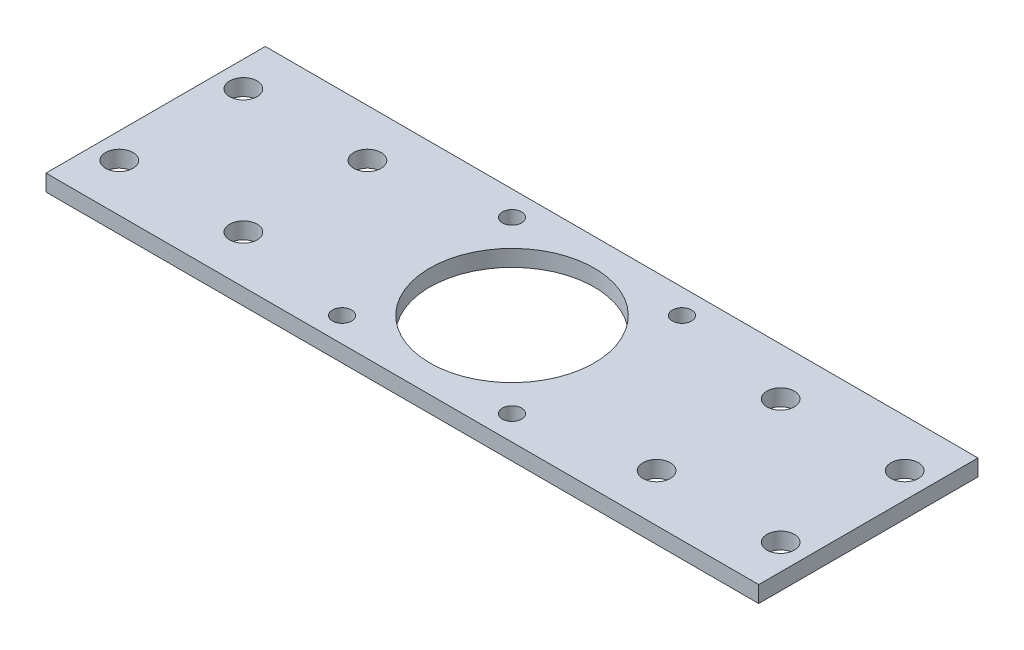
SolidWorks part; units mm, degrees
ref_plane "Front Plane" through (0, 0, 0) normal (0, 0, 1) x (1, 0, 0)
ref_plane "Top Plane" through (0, 0, 0) normal (0, 1, 0) x (1, 0, 0)
ref_plane "Right Plane" through (0, 0, 0) normal (1, 0, 0) x (0, 0, -1)
sketch "Sketch1" plane through (0, 0, 0) normal (0, 1, 0) x (1, 0, 0)
  line L1 (-65, 20) -> (65, 20)
  line L2 (-65, 20) -> (-65, -20)
  line L3 (-65, -20) -> (65, -20)
  line L4 (65, 20) -> (65, -20)
  line L5 (-65, 20) -> (65, -20) construction
  line L6 (-65, -20) -> (65, 20) construction
  point P0 (0, 0)
  dimension "D1" = 130
  dimension "D2" = 40
extrude "Boss-Extrude1" add sketch "Sketch1" along normal blind 3
sketch "Sketch2" plane through (0, 0, 0) normal (0, 1, 0) x (1, 0, 0)
  line L0 (65, 20) -> (-65, 20) construction
  line L1 (0, 0) -> (-49, 0) construction
  line L2 (-65, 20) -> (-65, -20) construction
  line L3 (-60.3137, 11.3137) -> (-37.6863, 11.3137) construction
  line L4 (-60.3137, 11.3137) -> (-60.3137, -11.3137) construction
  line L5 (-60.3137, -11.3137) -> (-37.6863, -11.3137) construction
  line L6 (-37.6863, 11.3137) -> (-37.6863, -11.3137) construction
  line L7 (-60.3137, 11.3137) -> (-37.6863, -11.3137) construction
  line L8 (-60.3137, -11.3137) -> (-37.6863, 11.3137) construction
  circle A0 centre (0, 0) radius 15
  circle A1 centre (-49, 0) radius 16 construction
  dimension "D2" = 30
  dimension "D3" = 32
  dimension "D1" = 20
extrude "Cut-Extrude1" cut sketch "Sketch2" along normal through all
hole_wizard "Ø5.0 (5) Diameter Hole1" positions "Sketch4" profile "Sketch3" hole size "Ø5.0" standard "ANSI Metric" end condition through all
sketch "Sketch4" plane through (0, 0, 0) normal (0, -1, 0) x (-1, 0, 0)
  point P0 (60.3137, 11.3137)
  point P2 (60.3137, -11.3137)
  point P4 (37.6863, -11.3137)
  point P6 (37.6863, 11.3137)
sketch "Sketch3" plane through (-60.3137, 0, -11.3137) normal (1, 0, 0) x (0, 0, -1)
  line L0 (0, 0) -> (0, 3)
  line L1 (0, 3) -> (2.5, 3)
  line L2 (2.5, 3) -> (2.5, 0)
  line L5 (2.5, 0) -> (0, 0)
  line L11 (0, -6.35) -> (0, 107.95) construction
  dimension "Thru Hole Dia." = 5
  dimension "Thru Hole Depth" = 3
mirror "Mirror1" about plane through (0, 0, 0) normal (1, 0, 0) of "Ø5.0 (5) Diameter Hole1"
hole_wizard "Ø3.5 (3.5) Diameter Hole1" positions "Sketch6" profile "Sketch5" hole size "Ø3.5" standard "ANSI Metric" end condition through all
sketch "Sketch6" plane through (0, 0, 0) normal (0, -1, 0) x (-1, 0, 0)
  line L1 (15.5, -15.5) -> (-15.5, -15.5) construction
  line L2 (15.5, -15.5) -> (15.5, 15.5) construction
  line L3 (15.5, 15.5) -> (-15.5, 15.5) construction
  line L4 (-15.5, -15.5) -> (-15.5, 15.5) construction
  line L5 (15.5, -15.5) -> (-15.5, 15.5) construction
  line L6 (15.5, 15.5) -> (-15.5, -15.5) construction
  point P0 (0, 0)
  point P1 (-15.5, 15.5)
  point P72 (15.5, -15.5)
  point P73 (15.5, 15.5)
  point P74 (-15.5, -15.5)
  dimension "D1" = 31
  dimension "D2" = 31
sketch "Sketch5" plane through (0, 0, 0) normal (1, 0, 0) x (0, 0, -1)
  line L0 (0, 0) -> (0, 3)
  line L1 (0, 3) -> (1.75, 3)
  line L2 (1.75, 3) -> (1.75, 0)
  line L5 (1.75, 0) -> (0, 0)
  line L11 (0, -6.35) -> (0, 107.95) construction
  dimension "Thru Hole Dia." = 3.5
  dimension "Thru Hole Depth" = 3
equation "\"a\"= 130"
equation "\"b\"= 40"
equation "\"c\"= 3"
equation "\"D1@Boss-Extrude1\"=\"c\""
equation "\"D2@Sketch1\"=\"b\""
equation "\"D1@Sketch1\"=\"a\""
equation "\"D1@Sketch2\"=\"b\"/2"
